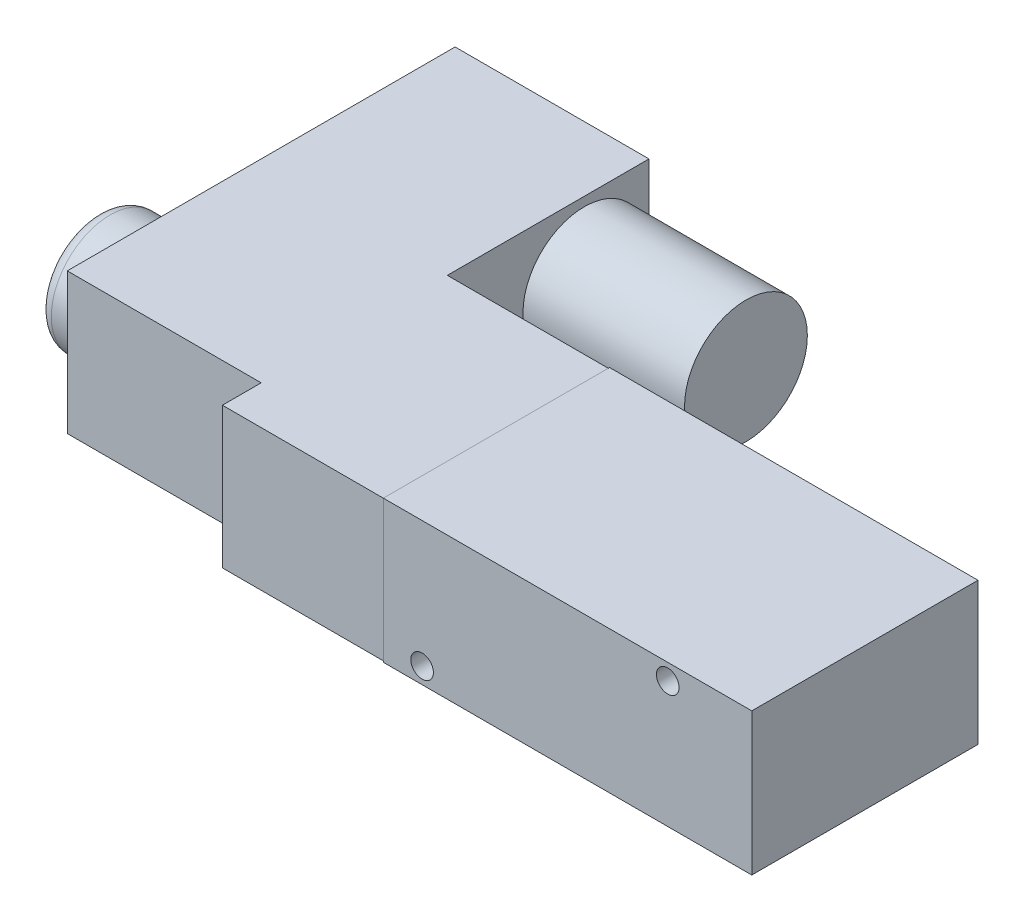
SolidWorks part; units mm, degrees
ref_plane "前视基准面" through (0, 0, 0) normal (0, 0, 1) x (1, 0, 0)
ref_plane "上视基准面" through (0, 0, 0) normal (0, 1, 0) x (1, 0, 0)
ref_plane "右视基准面" through (0, 0, 0) normal (1, 0, 0) x (0, 0, -1)
sketch "草图1" plane through (0, 0, 0) normal (0, 0, 1) x (1, 0, 0)
  line L1 (-25, 11) -> (25, 11)
  line L2 (-25, 11) -> (-25, -11)
  line L3 (-25, -11) -> (25, -11)
  line L4 (25, 11) -> (25, -11)
  line L5 (-25, 11) -> (25, -11) construction
  line L6 (-25, -11) -> (25, 11) construction
  point P1 (0, 0)
  dimension "D1" = 50
  dimension "D2" = 22
extrude "凸台-拉伸1" add sketch "草图1" along normal blind 35
sketch "草图2" plane through (0, 0, 0) normal (0, 0, -1) x (-1, 0, 0)
  circle A0 centre (-10, -1) radius 1.2797
  circle A1 centre (10, 1) radius 1.1647
  dimension "D5" = 2.3295
extrude "切除-拉伸1" cut sketch "草图2" against normal blind 10
hole_wizard "1/2-13 螺纹孔1" positions "草图4" profile "草图3" tap size "1/2-13" standard "Superior"
sketch "草图4" plane through (0, 0, 0) normal (0, 0, -1) x (-1, 0, 0)
  point P1 (10, 1)
  point P4 (-10, -1)
sketch "草图3" plane through (-10, 1, 0) normal (1, 0, 0) x (0, 1, 0)
  line L0 (0, 0) -> (0, 34.4795)
  line L1 (0, 34.4795) -> (5.3581, 31.26)
  line L2 (5.3581, 31.26) -> (5.3581, 0)
  line L5 (5.3581, 0) -> (0, 0)
  line L10 (0, 34.4795) -> (-5.3581, 31.26) construction
  line L11 (0, -6.35) -> (0, 107.95) construction
  dimension "螺纹孔钻头直径" = 10.7163
  dimension "螺纹孔钻头深度" = 31.26
  dimension "导头角度" = 118
cosmetic thread "孔螺蚊线1" parameters "D1"=25.4, "D2"=12.7
cosmetic thread "孔螺蚊线2" parameters "D1"=25.4, "D2"=12.7
sketch "草图5" plane through (0, 0, 0) normal (0, 0, -1) x (-1, 0, 0)
  line L0 (25, -11) -> (-25, -11) construction
  line L1 (-25, 11) -> (25, 11) construction
  circle A0 centre (-19, 8.5) radius 1.75
  circle A1 centre (19, -8.5) radius 1.75
  dimension "D6" = 3.5
  dimension "D1" = 2.5
  dimension "D2" = 2.5
extrude "切除-拉伸2" cut sketch "草图5" against normal up to next
sketch "草图6" plane through (25, 0, 0) normal (1, 0, 0) x (0, 0, -1)
  line L4 (0, -11) -> (0, 11)
  line L5 (0, 11) -> (-35, 11)
  line L6 (-35, 11) -> (-35, -11)
  line L7 (-35, -11) -> (0, -11)
  line L8 (0, -11) -> (0, 11)
  line L9 (0, 11) -> (-35, 11)
  line L10 (-35, 11) -> (-35, -11)
  line L11 (-35, -11) -> (0, -11)
  dimension "D1" = 0
extrude "凸台-拉伸3" add sketch "草图6" along normal blind 7
sketch "草图7" plane through (-25, 0, 0) normal (-1, 0, 0) x (0, 0, 1)
  line L16 (0.1, 10.9) -> (0.1, -10.9)
  line L17 (0.1, -10.9) -> (34.9, -10.9)
  line L18 (34.9, -10.9) -> (34.9, 10.9)
  line L19 (34.9, 10.9) -> (0.1, 10.9)
  line L20 (0.1, 10.9) -> (0.1, -10.9)
  line L21 (0.1, -10.9) -> (34.9, -10.9)
  line L22 (34.9, -10.9) -> (34.9, 10.9)
  line L23 (34.9, 10.9) -> (0.1, 10.9)
  dimension "D2" = 0.1
extrude "凸台-拉伸4" add sketch "草图7" along normal blind 25
sketch "草图8" plane through (-50, 0, 0) normal (-1, 0, 0) x (0, 0, 1)
  line L1 (-31.1, -10.9) -> (-31.1, 10.9)
  line L2 (28.9, -10.9) -> (28.9, 10.9)
  line L3 (28.9, -10.9) -> (28.9, 10.9)
  line L4 (-31.1, -10.9) -> (28.9, -10.9)
  line L5 (-31.1, 10.9) -> (28.9, 10.9)
  dimension "D1" = 6
  dimension "D2" = 60
extrude "凸台-拉伸5" add sketch "草图8" along normal blind 30
sketch "草图9" plane through (-50, 0, 0) normal (1, 0, 0) x (0, 0, -1)
  line L0 (31.1, 10.9) -> (31.1, -10.9) construction
  circle A0 centre (21.1, 0) radius 9.5
  point P2 (31.1, 0)
  dimension "D2" = 19
  dimension "D1" = 10
extrude "凸台-拉伸6" add sketch "草图9" along normal blind 25
sketch "草图10" plane through (-80, 0, 0) normal (-1, 0, 0) x (0, 0, 1)
  circle A0 centre (16.2803, 0) radius 9.0841
extrude "凸台-拉伸7" add sketch "草图10" along normal blind 8
fillet "圆角1" radius 2 1 edges at (-88, 0, 25.3644)
